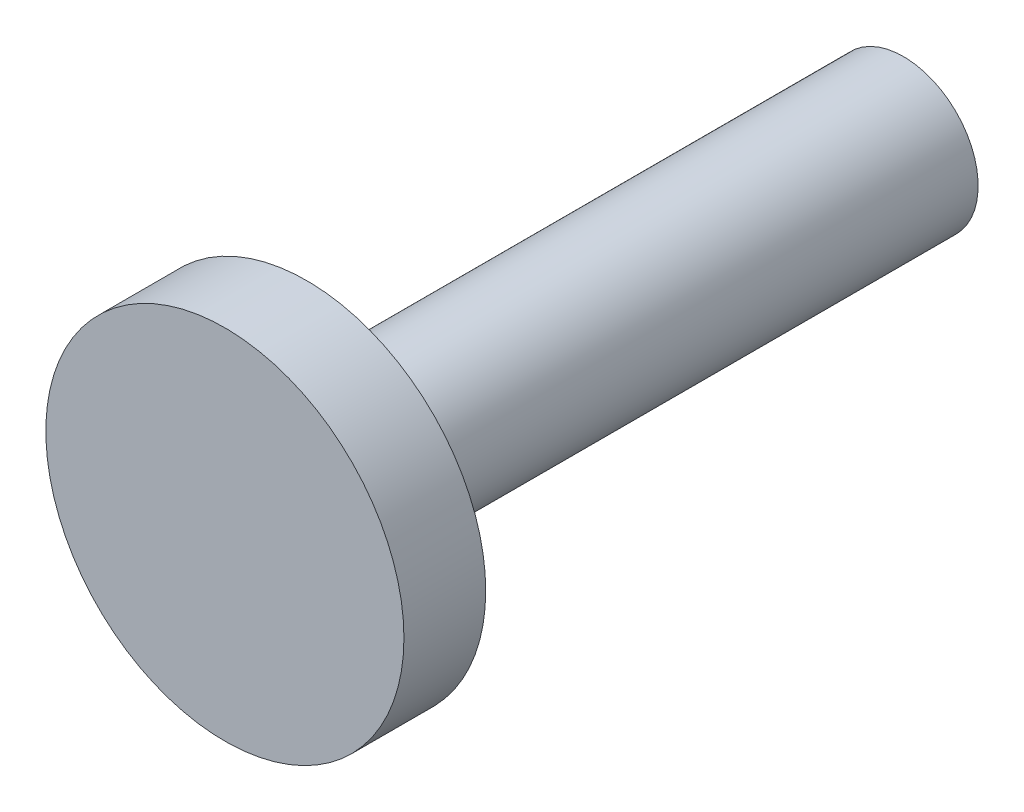
SolidWorks part; units mm, degrees
ref_plane "Plan de face" through (0, 0, 0) normal (0, 0, 1) x (1, 0, 0)
ref_plane "Plan de dessus" through (0, 0, 0) normal (0, 1, 0) x (1, 0, 0)
ref_plane "Plan de droite" through (0, 0, 0) normal (1, 0, 0) x (0, 0, -1)
sketch "Esquisse1" plane through (0, 0, 0) normal (0, 0, 1) x (1, 0, 0)
  circle A0 centre (0, 0) radius 3
  dimension "D1" = 6
extrude "Boss.-Extru.1" add sketch "Esquisse1" along normal blind 1.37
sketch "Esquisse2" plane through (0, 0, 0) normal (0, 0, -1) x (-1, 0, 0)
  circle A0 centre (0, 0) radius 1.25
  dimension "D1" = 2.5
extrude "Boss.-Extru.2" add sketch "Esquisse2" along normal blind 10
